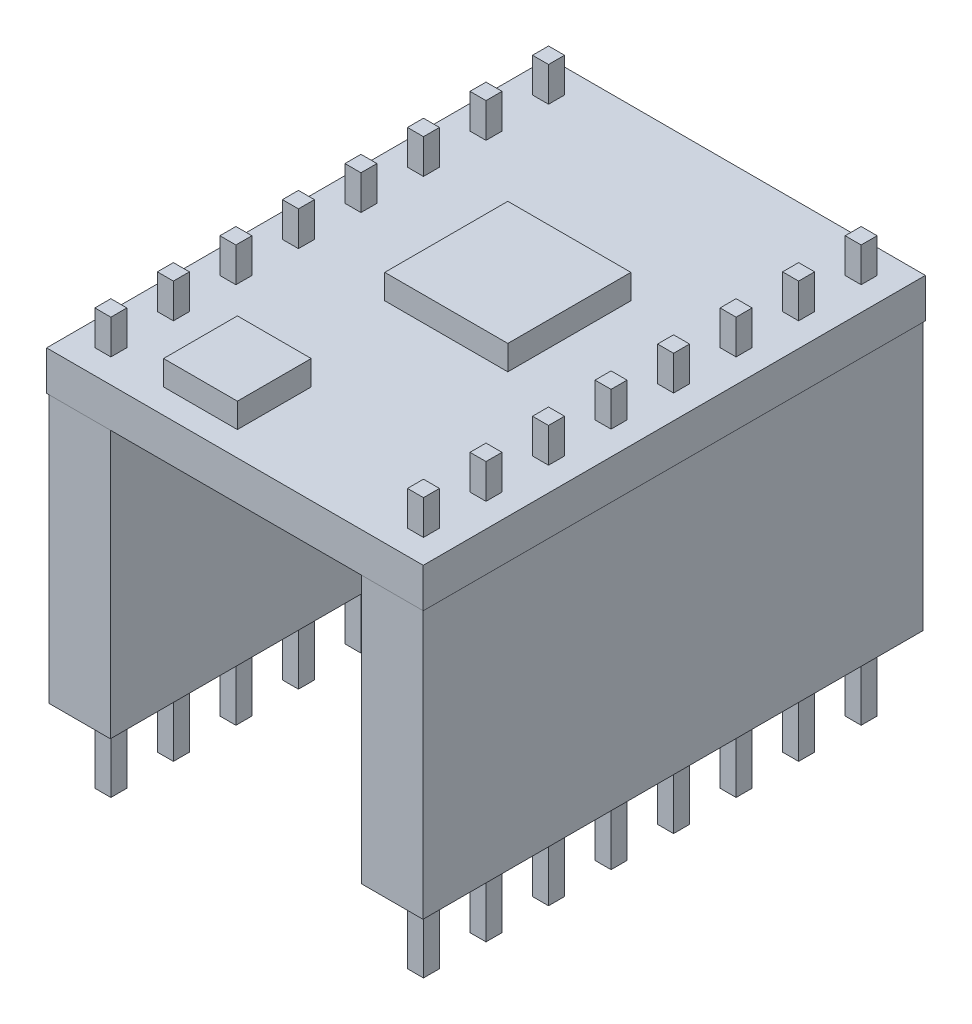
SolidWorks part; units mm, degrees
ref_plane "Plan de face" through (0, 0, 0) normal (0, 0, 1) x (1, 0, 0)
ref_plane "Plan de dessus" through (0, 0, 0) normal (0, 1, 0) x (1, 0, 0)
ref_plane "Plan de droite" through (0, 0, 0) normal (1, 0, 0) x (0, 0, -1)
sketch "Esquisse1" plane through (0, 0, 0) normal (0, 1, 0) x (1, 0, 0)
  line L1 (-7.65, 10.2) -> (7.65, 10.2)
  line L2 (-7.65, 10.2) -> (-7.65, -10.2)
  line L3 (-7.65, -10.2) -> (7.65, -10.2)
  line L4 (7.65, 10.2) -> (7.65, -10.2)
  point P4 (0, 10.2)
  point P6 (-7.65, 0)
  dimension "D1" = 15.3
  dimension "D2" = 20.4
extrude "Boss.-Extru.1" add sketch "Esquisse1" along normal blind 1.6
sketch "Esquisse2" plane through (0, 0, 0) normal (0, 1, 0) x (1, 0, 0)
  line L0 (0, 0) -> (0, 3.453) construction
  line L1 (-7.6, 10.16) -> (-5.1, 10.16)
  line L2 (-7.6, 10.16) -> (-7.6, -10.16)
  line L3 (-7.6, -10.16) -> (-5.1, -10.16)
  line L4 (-5.1, 10.16) -> (-5.1, -10.16)
  line L5 (5.1, 10.16) -> (5.1, -10.16)
  line L6 (7.6, -10.16) -> (5.1, -10.16)
  line L7 (7.6, 10.16) -> (7.6, -10.16)
  line L8 (7.6, 10.16) -> (5.1, 10.16)
  line L9 (-5.1, 0) -> (0, 0) construction
  point P12 (-6.35, 10.16)
  point P13 (6.35, 10.16)
  dimension "D1" = 20.32
  dimension "D2" = 2.5
  dimension "D3" = 12.7
extrude "Boss.-Extru.2" add sketch "Esquisse2" against normal blind 10.9
sketch "Esquisse3" plane through (0, -10.9, 0) normal (0, -1, 0) x (1, 0, 0)
  line L0 (-6.35, 10.16) -> (-6.35, -10.16) construction
  line L1 (-6.675, 1.595) -> (-6.025, 1.595)
  line L2 (-6.675, 1.595) -> (-6.675, 0.945)
  line L3 (-6.675, 0.945) -> (-6.025, 0.945)
  line L4 (-6.025, 1.595) -> (-6.025, 0.945)
  line L5 (-7.6, 10.16) -> (-5.1, 10.16) construction
  line L6 (-5.1, -10.16) -> (-7.6, -10.16) construction
  line L7 (0, 0) -> (1.7145, 0) construction
  line L8 (0, 0) -> (0, 3.3325) construction
  line L9 (-6.675, -0.945) -> (-6.025, -0.945)
  line L10 (-6.675, -1.595) -> (-6.025, -1.595)
  line L11 (-6.675, -1.595) -> (-6.675, -0.945)
  line L12 (-6.025, -1.595) -> (-6.025, -0.945)
  line L13 (-6.675, 4.135) -> (-6.675, 3.485)
  line L14 (-6.675, 4.135) -> (-6.025, 4.135)
  line L15 (-6.025, 4.135) -> (-6.025, 3.485)
  line L16 (-6.675, 3.485) -> (-6.025, 3.485)
  line L17 (-6.675, 6.675) -> (-6.675, 6.025)
  line L18 (-6.675, 6.675) -> (-6.025, 6.675)
  line L19 (-6.025, 6.675) -> (-6.025, 6.025)
  line L20 (-6.675, 6.025) -> (-6.025, 6.025)
  line L21 (-6.675, 9.215) -> (-6.675, 8.565)
  line L22 (-6.675, 9.215) -> (-6.025, 9.215)
  line L23 (-6.025, 9.215) -> (-6.025, 8.565)
  line L24 (-6.675, 8.565) -> (-6.025, 8.565)
  line L25 (-6.675, -9.215) -> (-6.025, -9.215)
  line L26 (-6.025, -9.215) -> (-6.025, -8.565)
  line L27 (-6.675, -8.565) -> (-6.025, -8.565)
  line L28 (-6.675, -9.215) -> (-6.675, -8.565)
  line L29 (-6.675, -6.675) -> (-6.025, -6.675)
  line L30 (-6.025, -6.675) -> (-6.025, -6.025)
  line L31 (-6.675, -6.025) -> (-6.025, -6.025)
  line L32 (-6.675, -6.675) -> (-6.675, -6.025)
  line L33 (-6.675, -4.135) -> (-6.025, -4.135)
  line L34 (-6.025, -4.135) -> (-6.025, -3.485)
  line L35 (-6.675, -4.135) -> (-6.675, -3.485)
  line L36 (-6.675, -3.485) -> (-6.025, -3.485)
  line L37 (6.675, -9.215) -> (6.675, -8.565)
  line L38 (6.675, -8.565) -> (6.025, -8.565)
  line L39 (6.025, -9.215) -> (6.025, -8.565)
  line L40 (6.675, -9.215) -> (6.025, -9.215)
  line L41 (6.675, -6.675) -> (6.675, -6.025)
  line L42 (6.675, -6.025) -> (6.025, -6.025)
  line L43 (6.025, -6.675) -> (6.025, -6.025)
  line L44 (6.675, -6.675) -> (6.025, -6.675)
  line L45 (6.675, -4.135) -> (6.675, -3.485)
  line L46 (6.675, -3.485) -> (6.025, -3.485)
  line L47 (6.025, -4.135) -> (6.025, -3.485)
  line L48 (6.675, -4.135) -> (6.025, -4.135)
  line L49 (6.675, 0.945) -> (6.025, 0.945)
  line L50 (6.025, 1.595) -> (6.025, 0.945)
  line L51 (6.675, 1.595) -> (6.025, 1.595)
  line L52 (6.675, 1.595) -> (6.675, 0.945)
  line L53 (6.675, -1.595) -> (6.675, -0.945)
  line L54 (6.675, -1.595) -> (6.025, -1.595)
  line L55 (6.025, -1.595) -> (6.025, -0.945)
  line L56 (6.675, -0.945) -> (6.025, -0.945)
  line L57 (6.675, 4.135) -> (6.025, 4.135)
  line L58 (6.025, 4.135) -> (6.025, 3.485)
  line L59 (6.675, 3.485) -> (6.025, 3.485)
  line L60 (6.675, 4.135) -> (6.675, 3.485)
  line L61 (6.675, 6.675) -> (6.025, 6.675)
  line L62 (6.025, 6.675) -> (6.025, 6.025)
  line L63 (6.675, 6.025) -> (6.025, 6.025)
  line L64 (6.675, 6.675) -> (6.675, 6.025)
  line L65 (6.675, 9.215) -> (6.025, 9.215)
  line L66 (6.025, 9.215) -> (6.025, 8.565)
  line L67 (6.675, 8.565) -> (6.025, 8.565)
  line L68 (6.675, 9.215) -> (6.675, 8.565)
  point P4 (-6.35, 1.595)
  point P19 (-6.675, -1.27)
  point P20 (-6.675, 1.27)
  dimension "D1" = 0.65
  dimension "D2" = 2.54
  dimension "D3" = 4
extrude "Boss.-Extru.3" add sketch "Esquisse3" along normal blind 3 and the other way blind 13.9
sketch "Esquisse4" plane through (0, 1.6, 0) normal (0, 1, 0) x (1, 0, 0)
  line L0 (-7.65, 10.2) -> (-7.65, -10.2) construction
  line L1 (-2.4381, 3.3245) -> (2.5619, 3.3245)
  line L2 (-2.4381, 3.3245) -> (-2.4381, -1.6755)
  line L3 (-2.4381, -1.6755) -> (2.5619, -1.6755)
  line L4 (2.5619, 3.3245) -> (2.5619, -1.6755)
  line L5 (-3.9, -6.2) -> (-0.9, -6.2)
  line L6 (-3.9, -6.2) -> (-3.9, -9.2)
  line L7 (-3.9, -9.2) -> (-0.9, -9.2)
  line L8 (-0.9, -6.2) -> (-0.9, -9.2)
  line L9 (-7.65, -10.2) -> (7.65, -10.2) construction
  dimension "D1" = 5
  dimension "D2" = 3
  dimension "D3" = 3.75
  dimension "D4" = 1
extrude "Boss.-Extru.4" add sketch "Esquisse4" along normal blind 1
